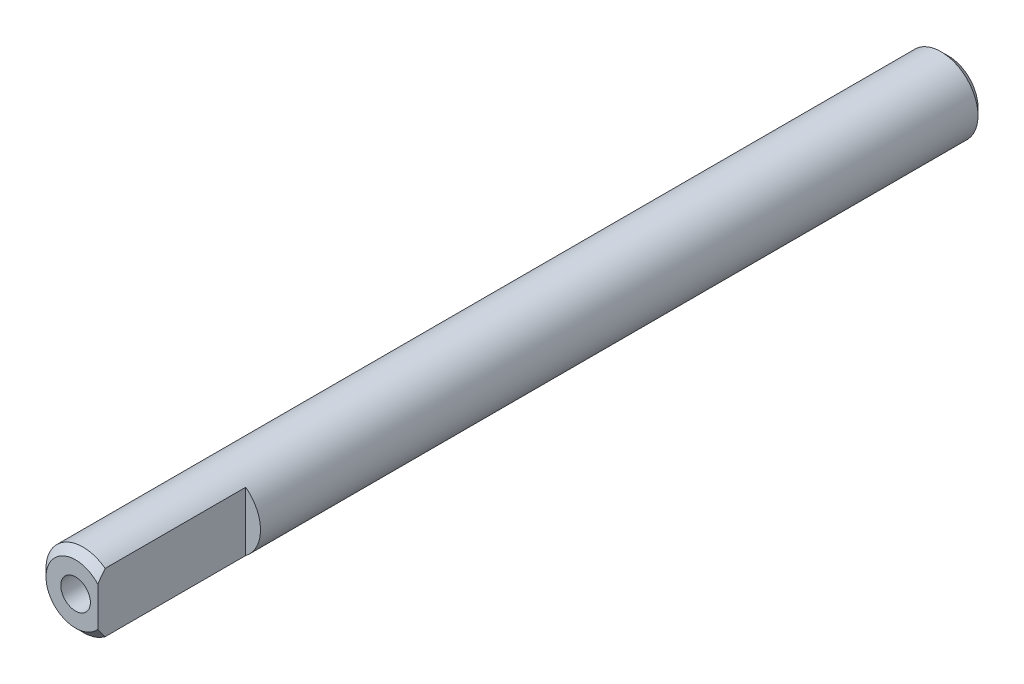
SolidWorks part; units mm, degrees
ref_plane "Front Plane" through (0, 0, 0) normal (0, 0, 1) x (1, 0, 0)
ref_plane "Top Plane" through (0, 0, 0) normal (0, 1, 0) x (1, 0, 0)
ref_plane "Right Plane" through (0, 0, 0) normal (1, 0, 0) x (0, 0, -1)
sketch "Sketch1" plane through (0, 0, 0) normal (0, 0, 1) x (1, 0, 0)
  circle A0 centre (0, 0) radius 2.5
  dimension "D1" = 5
extrude "Boss-Extrude1" add sketch "Sketch1" along normal blind 59
sketch "Sketch2" plane through (0, 0, 59) normal (0, 0, 1) x (1, 0, 0)
  circle A0 centre (0, 0) radius 1
  dimension "D1" = 2
extrude "Cut-Extrude1" cut sketch "Sketch2" against normal blind 10
chamfer "Chamfer1" distance 0.5 angle 45 2 edges at (2.5, 0, 0) (2.5, 0, 59)
sketch "Sketch3" plane through (0, 0, 59) normal (0, 0, 1) x (1, 0, 0)
  line L0 (-2.5, 2.0138) -> (-2.5, -2.6727) construction
  line L1 (1.5, 2.0138) -> (1.5, -2.6727)
  line L2 (1.5, 2.0138) -> (3.0301, 2.0138)
  line L3 (3.0301, 2.0138) -> (3.0301, -2.6727)
  line L4 (3.0301, -2.6727) -> (1.5, -2.6727)
  circle A0 centre (0, 0) radius 2.5 construction
  dimension "D1" = 4
extrude "Cut-Extrude2" cut sketch "Sketch3" against normal blind 10
